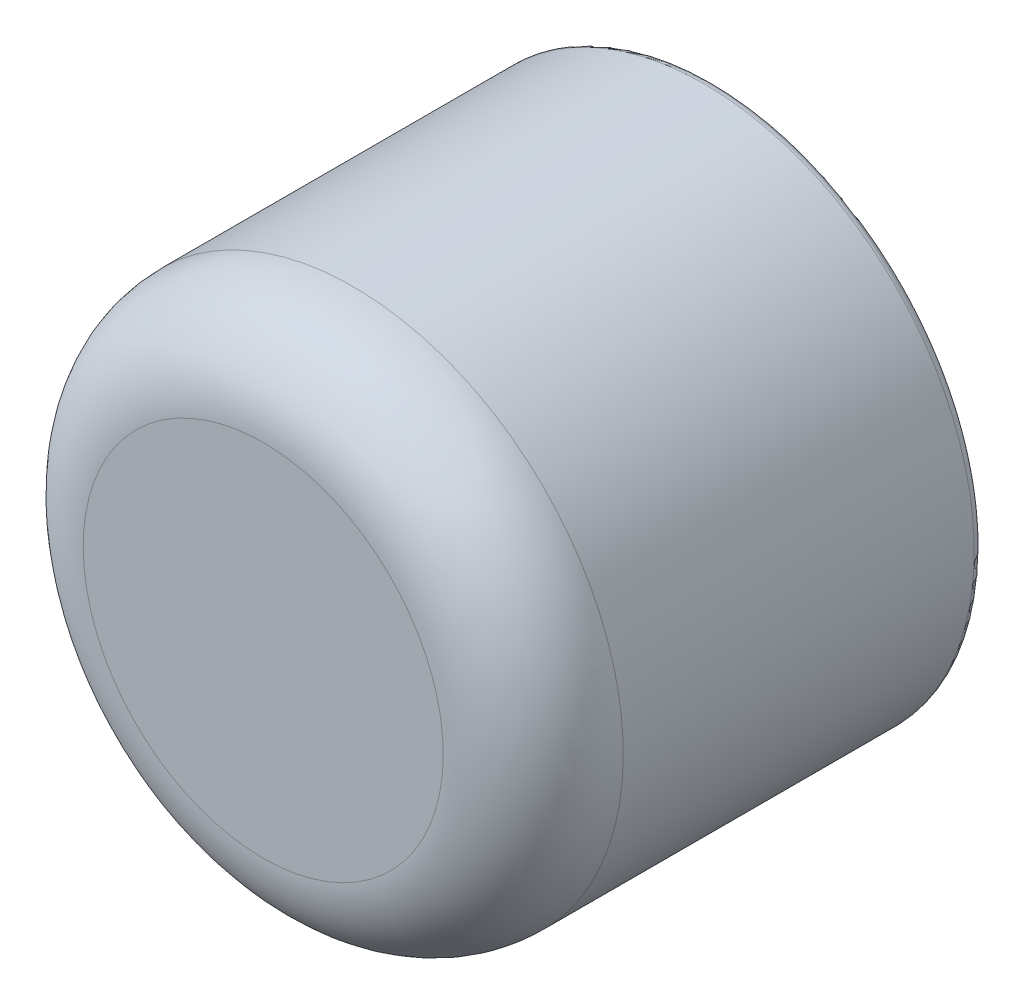
SolidWorks part; units mm, degrees
material "Glass"
ref_plane "Front Plane" through (0, 0, 0) normal (1, 0, 0) x (0, 1, 0)
ref_plane "Top Plane" through (0, 0, 0) normal (0, 0, 1) x (0, 1, 0)
ref_plane "Right Plane" through (0, 0, 0) normal (0, 1, 0) x (-1, 0, 0)
sketch "Sketch1" plane through (0, 0, 0) normal (1, 0, 0) x (0, 1, 0)
  line L0 (0, 22.327) -> (0, -25.4717) construction
  line L1 (-31.1552, 0) -> (25.2913, 0) construction
  line L2 (0, 12.5) -> (15, 12.5)
  line L3 (15, 12.5) -> (15, -12.5)
  line L4 (15, -12.5) -> (0, -12.5)
  line L5 (0, 12.5) -> (0, -12.5)
  point P7 (15, 0)
  dimension "D1" = 25
  dimension "D2" = 30
revolve "Revolve1" add sketch "Sketch1" angle 360 about L0
fillet "Fillet1" radius 5 1 edges at (0, -15, 12.5)
fillet "Fillet2" radius 0.5 1 edges at (0, -15, -12.5)
